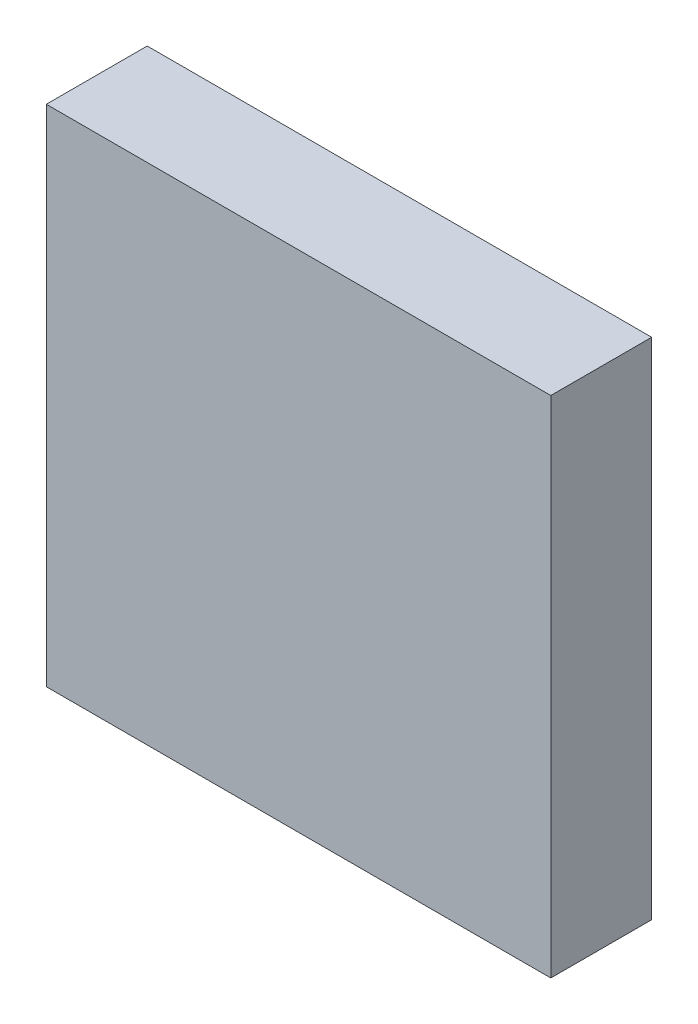
SolidWorks part; units mm, degrees
ref_plane "Front Plane" through (0, 0, 0) normal (0, 0, 1) x (1, 0, 0)
ref_plane "Top Plane" through (0, 0, 0) normal (0, 1, 0) x (1, 0, 0)
ref_plane "Right Plane" through (0, 0, 0) normal (1, 0, 0) x (0, 0, -1)
sketch "Sketch1" plane through (0, 0, 0) normal (0, 0, 1) x (1, 0, 0)
  line L1 (0, 0) -> (0.5, 0)
  line L2 (0, 0) -> (0, 0.5)
  line L3 (0, 0.5) -> (0.5, 0.5)
  line L4 (0.5, 0) -> (0.5, 0.5)
  dimension "D1" = 0.5
  dimension "D2" = 0.5
extrude "Boss-Extrude1" add sketch "Sketch1" along normal blind 0.1
